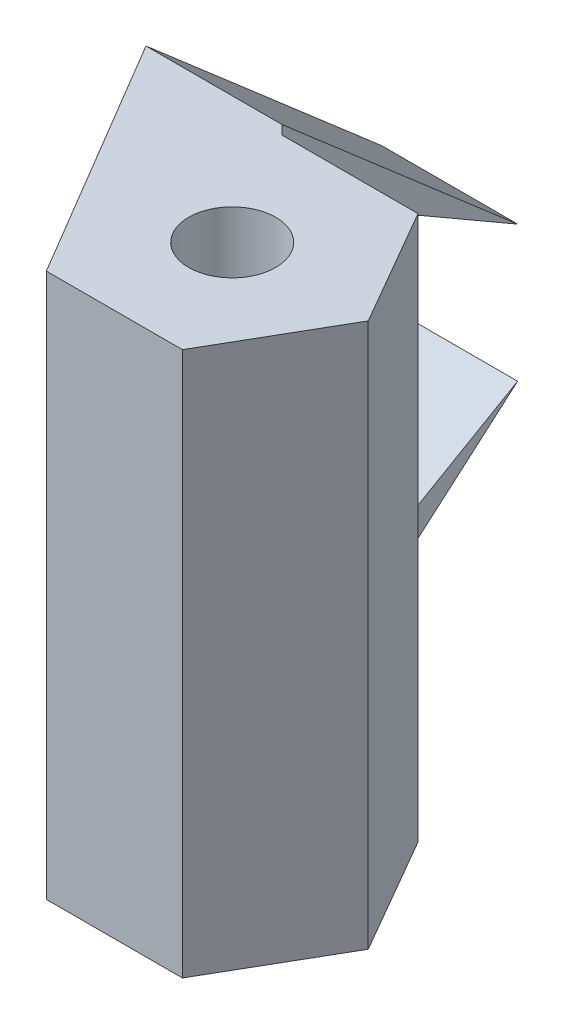
SolidWorks part; units mm, degrees
ref_plane "Front Plane" through (0, 0, 0) normal (0, 0, 1) x (1, 0, 0)
ref_plane "Top Plane" through (0, 0, 0) normal (0, 1, 0) x (1, 0, 0)
ref_plane "Right Plane" through (0, 0, 0) normal (1, 0, 0) x (0, 0, -1)
sketch "Sketch1" plane through (0, 0, 0) normal (0, 1, 0) x (1, 0, 0)
  line L1 (3.175, 5.4993) -> (-3.175, 5.4993)
  line L2 (-3.175, 5.4993) -> (-6.35, 0)
  line L3 (-6.35, 0) -> (-3.175, -5.4993)
  line L4 (-3.175, -5.4993) -> (3.175, -5.4993)
  line L5 (3.175, -5.4993) -> (6.35, 0)
  line L6 (6.35, 0) -> (3.175, 5.4993)
  circle A0 centre (0, 0) radius 5.4993 construction
  dimension "D1" = 6.35
extrude "Boss-Extrude1" add sketch "Sketch1" along normal blind 25.4
sketch "Sketch3" plane through (0, 25.4, 0) normal (0, 1, 0) x (1, 0, 0)
  circle A0 centre (0, 0) radius 2.032
  dimension "D1" = 4.064
extrude "Cut-Extrude1" cut sketch "Sketch3" against normal blind 25.4
sketch "Sketch2" plane through (0, 25.4, 0) normal (0, 1, 0) x (1, 0, 0)
  line L6 (-3.175, -5.4993) -> (-9.9504, 5.9246)
  line L7 (-3.175, 5.4993) -> (-3.6004, 5.9246)
  line L8 (3.175, 5.4993) -> (-3.175, 5.4993) construction
  line L9 (-3.175, 5.4993) -> (-6.35, 0) construction
  line L10 (-9.9504, 5.9246) -> (-3.6004, 5.9246)
  line L11 (-3.175, -5.4993) -> (-6.35, 0)
  line L12 (-6.35, 0) -> (-3.175, 5.4993)
  point P12 (-4.7625, 2.7496)
  dimension "D1" = 135
  dimension "D2" = 3.175
  dimension "D3" = 6.35
extrude "Boss-Extrude2" add sketch "Sketch2" against normal blind 25.4
ref_plane "Plane1" through (-9.9504, 0, 0) normal (-1, 0, 0) x (0, 0, 1)
sketch "Sketch5" plane through (-9.9504, 0, 0) normal (-1, 0, 0) x (0, 0, 1)
  line L0 (-5.9246, 0) -> (-5.9246, 25.4) construction
  line L1 (-5.9246, 9.525) -> (-5.9246, 15.875)
  line L2 (-5.9246, 15.875) -> (-11.4239, 19.05)
  line L3 (-11.4239, 19.05) -> (-16.9232, 15.875)
  line L4 (-16.9232, 15.875) -> (-16.9232, 9.525)
  line L5 (-16.9232, 9.525) -> (-11.4239, 6.35)
  line L6 (-11.4239, 6.35) -> (-5.9246, 9.525)
  line L7 (-16.9232, 15.875) -> (-5.9246, 25.4)
  line L8 (-16.9232, 9.525) -> (-5.9246, 0)
  line L9 (-5.9246, 0) -> (-5.9246, 9.525)
  line L10 (-5.9246, 15.875) -> (-5.9246, 25.4)
  circle A0 centre (-11.4239, 12.7) radius 5.4993 construction
  point P10 (-5.9246, 12.7)
  dimension "D1" = 12.7
  dimension "D2" = 6.35
extrude "Boss-Extrude4" add sketch "Sketch5" against normal blind 6.35 contours L2 L10 L7 L3 | L8 L9 L6 L5
